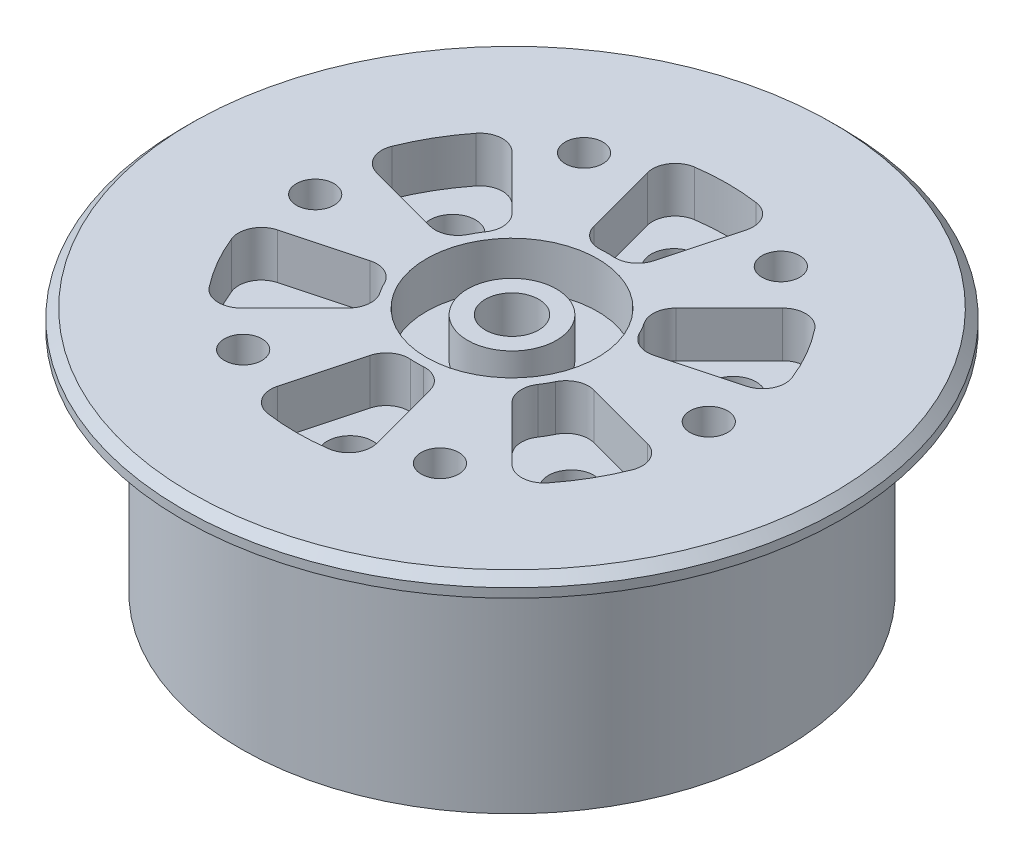
SolidWorks part; units mm, degrees
ref_plane "前视基准面" through (0, 0, 0) normal (0, 0, 1) x (1, 0, 0)
ref_plane "上视基准面" through (0, 0, 0) normal (0, 1, 0) x (1, 0, 0)
ref_plane "右视基准面" through (0, 0, 0) normal (1, 0, 0) x (0, 0, -1)
sketch "草图1" plane through (0, 0, 0) normal (0, 1, 0) x (1, 0, 0)
  circle A0 centre (0, 0) radius 28.9
  dimension "D1" = 57.8
extrude "凸台-拉伸1" add sketch "草图1" along normal blind 1.6 contours A0
chamfer "倒角1" distance 0.8 angle 45 1 edges at (0, 1.6, 28.9)
sketch "草图2" plane through (0, 0, 0) normal (0, -1, 0) x (1, 0, 0)
  circle A0 centre (0, 0) radius 23.75
  dimension "D1" = 47.5
extrude "凸台-拉伸2" add sketch "草图2" along normal blind 20 contours A0
sketch "草图3" plane through (0, 1.6, 0) normal (0, 1, 0) x (1, 0, 0)
  line L0 (0, 0) -> (50000, 0) construction
  line L1 (0, 0) -> (0, 50000) construction
  line L2 (0, 0) -> (43301.2702, 25000) construction
  line L3 (0, 0) -> (25000, 43301.2702) construction
  line L4 (0, 0) -> (43301.2702, -25000) construction
  line L5 (0, 0) -> (25000, -43301.2702) construction
  line L6 (-2.6283, 9.8089) -> (-4.3433, 16.2094)
  line L7 (2.6283, 9.8089) -> (4.3433, 16.2094)
  line L8 (9.8089, 2.6283) -> (16.2094, 4.3433)
  line L9 (7.1806, 7.1806) -> (11.8661, 11.8661)
  line L10 (7.1806, -7.1806) -> (11.8661, -11.8661)
  line L11 (9.8089, -2.6283) -> (16.2094, -4.3433)
  line L12 (-2.6283, -9.8089) -> (-4.3433, -16.2094)
  line L13 (2.6283, -9.8089) -> (4.3433, -16.2094)
  line L14 (-9.8089, -2.6283) -> (-16.2094, -4.3433)
  line L15 (-7.1806, -7.1806) -> (-11.8661, -11.8661)
  line L16 (-7.1806, 7.1806) -> (-11.8661, 11.8661)
  line L17 (-9.8089, 2.6283) -> (-16.2094, 4.3433)
  circle A0 centre (0, 0) radius 17.25 construction
  circle A1 centre (0, 0) radius 7.5
  circle A3 centre (0, 0) radius 18.9 construction
  arc A4 (-2.6968, 18.7066) -> (2.6968, 18.7066) centre (0, 0) cw
  arc A5 (-0.5619, 8.3311) -> (0.5619, 8.3311) centre (0, 0) cw
  arc A6 (7.4959, 3.679) -> (9.8089, 2.6283) centre (9.2913, 4.5601) ccw
  arc A7 (-2.6968, 18.7066) -> (-4.3433, 16.2094) centre (-2.4115, 16.7271) ccw
  arc A8 (2.6968, 18.7066) -> (4.3433, 16.2094) centre (2.4115, 16.7271) cw
  arc A9 (0.5619, 8.3311) -> (2.6283, 9.8089) centre (0.6964, 10.3265) ccw
  arc A10 (-0.5619, 8.3311) -> (-2.6283, 9.8089) centre (-0.6964, 10.3265) cw
  arc A11 (17.5488, 7.0178) -> (16.2094, 4.3433) centre (15.6918, 6.2752) cw
  arc A12 (14.852, 11.6888) -> (17.5488, 7.0178) centre (0, 0) cw
  arc A13 (14.852, 11.6888) -> (11.8661, 11.8661) centre (13.2803, 10.4519) ccw
  arc A14 (6.934, 4.6521) -> (7.1806, 7.1806) centre (8.5948, 5.7664) cw
  arc A15 (6.934, 4.6521) -> (7.4959, 3.679) centre (0, 0) cw
  arc A16 (6.934, -4.6521) -> (7.1806, -7.1806) centre (8.5948, -5.7664) ccw
  arc A17 (14.852, -11.6888) -> (11.8661, -11.8661) centre (13.2803, -10.4519) cw
  arc A18 (17.5488, -7.0178) -> (14.852, -11.6888) centre (0, 0) cw
  arc A19 (17.5488, -7.0178) -> (16.2094, -4.3433) centre (15.6918, -6.2752) ccw
  arc A20 (7.4959, -3.679) -> (9.8089, -2.6283) centre (9.2913, -4.5601) cw
  arc A21 (7.4959, -3.679) -> (6.934, -4.6521) centre (0, 0) cw
  arc A22 (-0.5619, -8.3311) -> (-2.6283, -9.8089) centre (-0.6964, -10.3265) ccw
  arc A23 (-2.6968, -18.7066) -> (-4.3433, -16.2094) centre (-2.4115, -16.7271) cw
  arc A24 (2.6968, -18.7066) -> (-2.6968, -18.7066) centre (0, 0) cw
  arc A25 (2.6968, -18.7066) -> (4.3433, -16.2094) centre (2.4115, -16.7271) ccw
  arc A26 (0.5619, -8.3311) -> (2.6283, -9.8089) centre (0.6964, -10.3265) cw
  arc A27 (0.5619, -8.3311) -> (-0.5619, -8.3311) centre (0, 0) cw
  arc A28 (-7.4959, -3.679) -> (-9.8089, -2.6283) centre (-9.2913, -4.5601) ccw
  arc A29 (-17.5488, -7.0178) -> (-16.2094, -4.3433) centre (-15.6918, -6.2752) cw
  arc A30 (-14.852, -11.6888) -> (-17.5488, -7.0178) centre (0, 0) cw
  arc A31 (-14.852, -11.6888) -> (-11.8661, -11.8661) centre (-13.2803, -10.4519) ccw
  arc A32 (-6.934, -4.6521) -> (-7.1806, -7.1806) centre (-8.5948, -5.7664) cw
  arc A33 (-6.934, -4.6521) -> (-7.4959, -3.679) centre (0, 0) cw
  arc A34 (-6.934, 4.6521) -> (-7.1806, 7.1806) centre (-8.5948, 5.7664) ccw
  arc A35 (-14.852, 11.6888) -> (-11.8661, 11.8661) centre (-13.2803, 10.4519) cw
  arc A36 (-17.5488, 7.0178) -> (-14.852, 11.6888) centre (0, 0) cw
  arc A37 (-17.5488, 7.0178) -> (-16.2094, 4.3433) centre (-15.6918, 6.2752) ccw
  arc A38 (-7.4959, 3.679) -> (-9.8089, 2.6283) centre (-9.2913, 4.5601) cw
  arc A39 (-7.4959, 3.679) -> (-6.934, 4.6521) centre (0, 0) cw
  point P16 (-17.25, 0)
  point P17 (-8.625, 14.9389)
  point P18 (8.625, 14.9389)
  point P19 (17.25, 0)
  point P20 (8.625, -14.9389)
  point P21 (-8.625, -14.9389)
  point P31 (-4.8917, 18.256)
  point P99 (0, 0)
  dimension "D5" = 34.5
  dimension "D6" = 15
  dimension "D7" = 1.65
  dimension "D8" = 8.35
  dimension "D9" = 2
  dimension "D1" = 30
  dimension "D2" = 30
  dimension "D3" = 30
  dimension "D4" = 30
  dimension "D10" = 15
  dimension "D11" = 15
  dimension "D12" = 6
hole_wizard "M4 螺纹孔的螺纹孔钻头1" positions "草图4" profile "草图5" hole size "M4" standard "GB"
sketch "草图4" plane through (0, 1.6, 0) normal (0, 1, 0) x (1, 0, 0)
  point P0 (-17.25, 0)
  point P3 (-8.625, 14.9389)
  point P6 (8.625, 14.9389)
  point P9 (17.25, 0)
  point P12 (8.625, -14.9389)
  point P15 (-8.625, -14.9389)
sketch "草图5" plane through (-17.25, 1.6, 0) normal (1, 0, 0) x (0, 0, 1)
  line L0 (0, 0) -> (0, 10)
  line L1 (0, 10) -> (1.65, 9.0086)
  line L2 (1.65, 9.0086) -> (1.65, 0)
  line L5 (1.65, 0) -> (0, 0)
  line L10 (0, 10) -> (-1.65, 9.0086) construction
  line L11 (0, -6.35) -> (0, 107.95) construction
  dimension "孔直径" = 3.3
  dimension "孔深度" = 10
  dimension "导头角度" = 118
extrude "切除-拉伸1" cut sketch "草图3" against normal blind 4 contours A1 | L7 A8 A4 A7 L6 A10 A5 A9 | L16 A35 A36 A37 L17 A38 A39 A34 | L8 A11 A12 A13 L9 A14 A15 A6 | L10 A17 A18 A19 L11 A20 A21 A16 | L12 A23 A24 A25 L13 A26 A27 A22 | L14 A29 A30 A31 L15 A32 A33 A28
sketch "草图7" plane through (0, -2.4, 0) normal (0, 1, 0) x (1, 0, 0)
  circle A0 centre (0, 0) radius 3.9
  dimension "D1" = 7.8
extrude "凸台-拉伸3" add sketch "草图7" along normal blind 3.5 contours A0
sketch "草图8" plane through (0, 1.1, 0) normal (0, 1, 0) x (1, 0, 0)
  circle A0 centre (0, 0) radius 2.34
  dimension "D1" = 4.68
extrude "切除-拉伸2" cut sketch "草图8" against normal blind 10 contours A0
sketch "草图9" plane through (0, -2.4, 0) normal (0, 1, 0) x (1, 0, 0)
  line L2 (-14.852, 11.6888) -> (-12.2976, 7.1) construction
  line L3 (-12.2976, 7.1) -> (-17.5488, 7.0178) construction
  circle A0 centre (-12.2976, 7.1) radius 2
  circle A1 centre (0, 0) radius 14.2 construction
  circle A2 centre (0, 14.2) radius 2
  circle A3 centre (12.2976, 7.1) radius 2
  circle A4 centre (12.2976, -7.1) radius 2
  circle A5 centre (0, -14.2) radius 2
  circle A6 centre (-12.2976, -7.1) radius 2
  point P5 (0, 0)
  point P7 (-0.676, 16.6805)
  point P21 (0, 0)
  point P22 (0, 0)
  dimension "D1" = 4
  dimension "D2" = 28.4
  dimension "D3" = 6
extrude "切除-拉伸3" cut sketch "草图9" against normal blind 10
